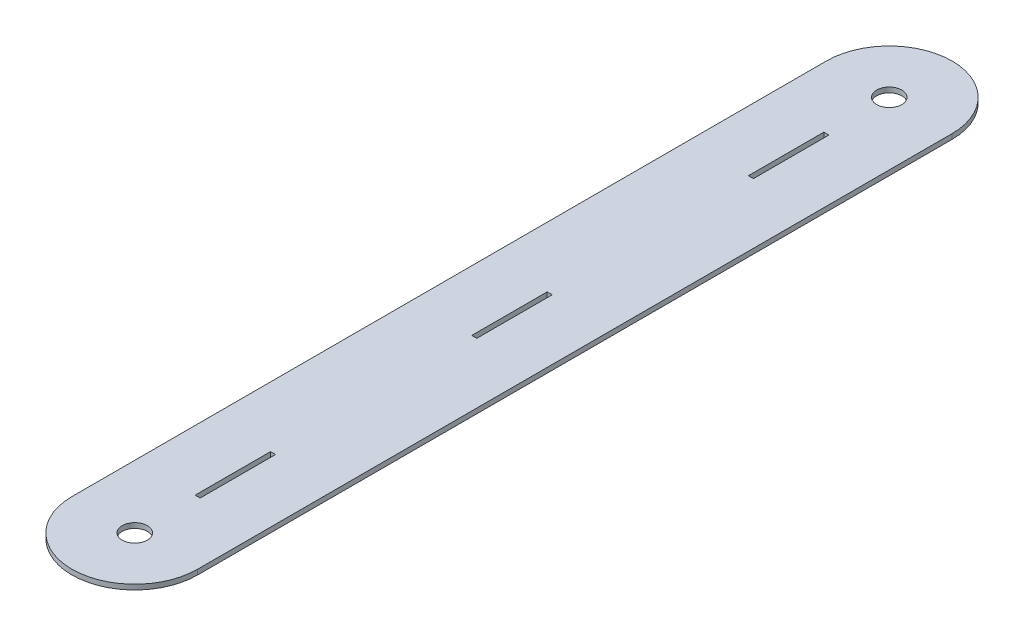
SolidWorks part; units mm, degrees
ref_plane "Front Plane" through (0, 0, 0) normal (0, 0, 1) x (1, 0, 0)
ref_plane "Top Plane" through (0, 0, 0) normal (0, 1, 0) x (1, 0, 0)
ref_plane "Right Plane" through (0, 0, 0) normal (1, 0, 0) x (0, 0, -1)
sketch "Sketch1" plane through (0, 0, 0) normal (0, 1, 0) x (1, 0, 0)
  line L0 (0, 150) -> (0, 0) construction
  line L1 (12.5, 150) -> (12.5, 0)
  line L4 (-12.5, 150) -> (-12.5, 0)
  line L5 (0, 20) -> (-20.2876, 20) construction
  line L6 (-0.5, 82.5) -> (0.5, 82.5)
  line L7 (-0.5, 82.5) -> (-0.5, 67.5)
  line L8 (-0.5, 67.5) -> (0.5, 67.5)
  line L9 (0.5, 82.5) -> (0.5, 67.5)
  line L10 (-0.5, 82.5) -> (0.5, 67.5) construction
  line L11 (-0.5, 67.5) -> (0.5, 82.5) construction
  line L12 (-0.5, 12.5) -> (0.5, 12.5)
  line L13 (-0.5, 12.5) -> (-0.5, 27.5)
  line L14 (-0.5, 27.5) -> (0.5, 27.5)
  line L15 (0.5, 12.5) -> (0.5, 27.5)
  line L16 (-0.5, 12.5) -> (0.5, 27.5) construction
  line L17 (-0.5, 27.5) -> (0.5, 12.5) construction
  line L18 (-0.5, 137.5) -> (0.5, 137.5)
  line L19 (-0.5, 137.5) -> (-0.5, 122.5)
  line L20 (-0.5, 122.5) -> (0.5, 122.5)
  line L21 (0.5, 137.5) -> (0.5, 122.5)
  line L22 (-0.5, 137.5) -> (0.5, 122.5) construction
  line L23 (-0.5, 122.5) -> (0.5, 137.5) construction
  line L24 (-20.2876, 20) -> (-20.2876, 75) construction
  line L25 (-20.2876, 75) -> (0, 75) construction
  line L26 (0, 130) -> (-20.2876, 130) construction
  line L27 (-20.2876, 130) -> (-20.2876, 75) construction
  arc A5 (12.5, 150) -> (-12.5, 150) centre (0, 150) ccw
  arc A6 (-12.5, 0) -> (12.5, 0) centre (0, 0) ccw
  circle A7 centre (0, 0) radius 2.5
  circle A8 centre (0, 150) radius 2.5
  point P3 (0, 75)
  point P12 (0, 75)
  point P18 (0, 20)
  point P23 (0, 130)
  dimension "D3" = 5
  dimension "D1" = 150
  dimension "D2" = 25
  dimension "D4" = 55
  dimension "D5" = 55
  dimension "D6" = 15
  dimension "D7" = 1
extrude "Boss-Extrude1" add sketch "Sketch1" along normal blind 1
